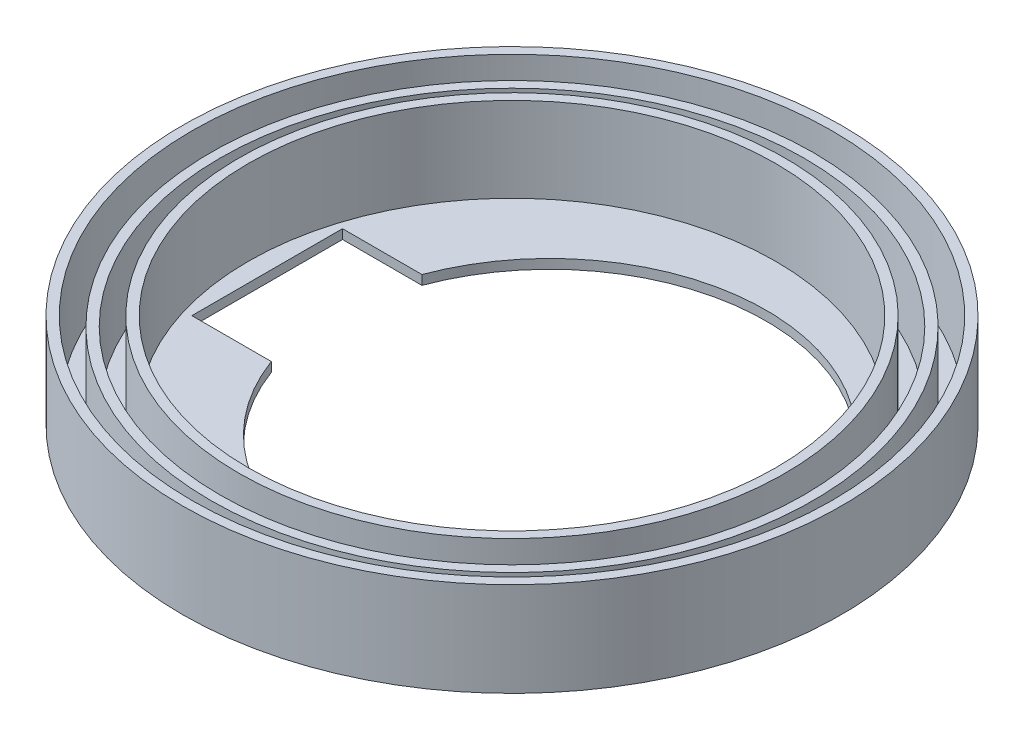
SolidWorks part; units mm, degrees
ref_plane "Front Plane" through (0, 0, 0) normal (0, 0, 1) x (1, 0, 0)
ref_plane "Top Plane" through (0, 0, 0) normal (0, 1, 0) x (1, 0, 0)
ref_plane "Right Plane" through (0, 0, 0) normal (1, 0, 0) x (0, 0, -1)
sketch "Sketch1" plane through (0, 0, 0) normal (0, 1, 0) x (1, 0, 0)
  circle A0 centre (0, 0) radius 17.5
extrude "Boss-Extrude1" add sketch "Sketch1" along normal blind 0.5
sketch "Sketch2" plane through (0, 0.5, 0) normal (0, 1, 0) x (1, 0, 0)
  circle A0 centre (2, 0) radius 11.5
extrude "Cut-Extrude1" cut sketch "Sketch2" against normal blind 0.5
sketch "Sketch3" plane through (0, 0, 0) normal (0, 1, 0) x (1, 0, 0)
  line L1 (2, 4) -> (-13, 4)
  line L2 (2, 4) -> (2, -4)
  line L3 (2, -4) -> (-13, -4)
  line L4 (-13, 4) -> (-13, -4)
extrude "Cut-Extrude4" cut sketch "Sketch3" along normal blind 2.5
sketch "Sketch4" plane through (0, 0, 0) normal (0, 1, 0) x (1, 0, 0)
  circle A0 centre (0, 0) radius 16
  circle A1 centre (0, 0) radius 15.5
extrude "Boss-Extrude2" add sketch "Sketch4" along normal blind 4.5
sketch "Sketch5" plane through (0, 0.5, 0) normal (0, 1, 0) x (1, 0, 0)
  circle A0 centre (0, 0) radius 14.5
  circle A1 centre (0, 0) radius 14.5
  circle A2 centre (0, 0) radius 14
extrude "Boss-Extrude3" add sketch "Sketch5" along normal blind 4.5 contours A0 | A2
sketch "Sketch6" plane through (0, 0.5, 0) normal (0, 1, 0) x (1, 0, 0)
  circle A0 centre (0, 0) radius 17.5
  circle A1 centre (0, 0) radius 17
extrude "Boss-Extrude4" add sketch "Sketch6" along normal blind 4.5
